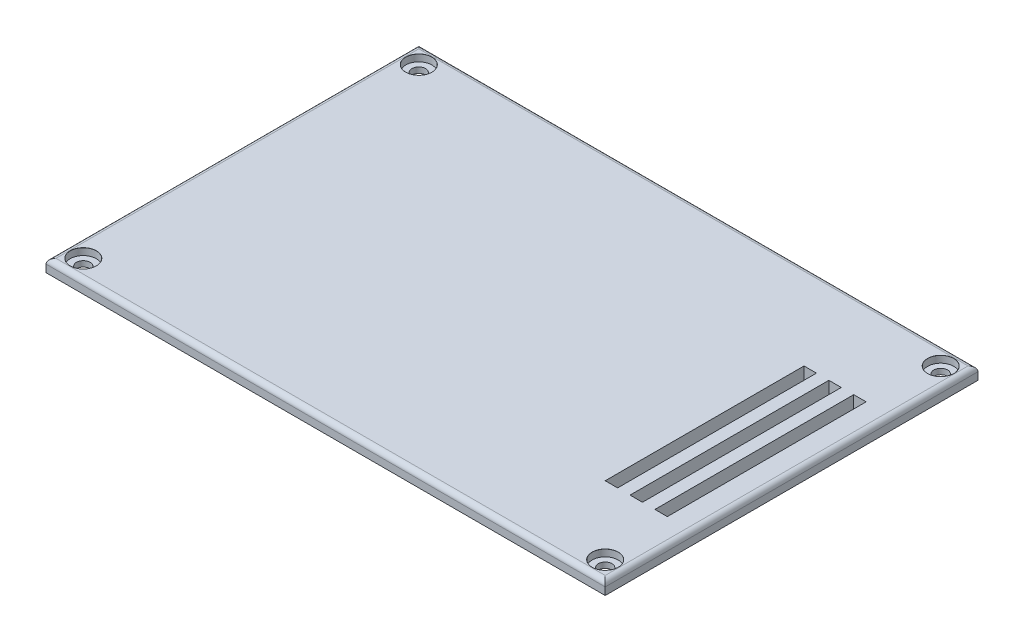
SolidWorks part; units mm, degrees
ref_plane "Front Plane" through (0, 0, 0) normal (0, 0, 1) x (1, 0, 0)
ref_plane "Top Plane" through (0, 0, 0) normal (0, 1, 0) x (1, 0, 0)
ref_plane "Right Plane" through (0, 0, 0) normal (1, 0, 0) x (0, 0, -1)
sketch "Sketch1" plane through (0, 0, 0) normal (0, 1, 0) x (1, 0, 0)
  line L1 (-112.5, 75) -> (112.5, 75)
  line L2 (-112.5, 75) -> (-112.5, -75)
  line L3 (-112.5, -75) -> (112.5, -75)
  line L4 (112.5, 75) -> (112.5, -75)
  line L5 (-112.5, 75) -> (112.5, -75) construction
  line L6 (-112.5, -75) -> (112.5, 75) construction
  line L7 (97.5, 40) -> (102.5, 40)
  line L8 (97.5, 40) -> (97.5, -40)
  line L9 (97.5, -40) -> (102.5, -40)
  line L10 (102.5, 40) -> (102.5, -40)
  line L11 (87.5, 40) -> (92.5, 40)
  line L12 (87.5, 40) -> (87.5, -40)
  line L13 (87.5, -40) -> (92.5, -40)
  line L14 (92.5, 40) -> (92.5, -40)
  line L15 (77.5, 40) -> (82.5, 40)
  line L16 (77.5, 40) -> (77.5, -40)
  line L17 (77.5, -40) -> (82.5, -40)
  line L18 (82.5, 40) -> (82.5, -40)
  point P0 (0, 0)
  point P18 (0, 0)
  point P19 (0, 0)
  point P20 (102.5, 0)
  point P21 (112.5, 0)
  dimension "D1" = 150
  dimension "D2" = 225
  dimension "D3" = 80
  dimension "D4" = 5
  dimension "D5" = 5
  dimension "D6" = 5
  dimension "D7" = 10
extrude "Boss-Extrude1" add sketch "Sketch1" along normal blind 5
hole_wizard "CBORE for M5 SBHCS1" positions "Sketch2" profile "Sketch3" counterbore size "M5" standard "ANSI Metric" end condition through all
sketch "Sketch2" plane through (0, 5, 0) normal (0, 1, 0) x (1, 0, 0)
  line L1 (-105, 67.5) -> (105, 67.5) construction
  line L2 (105, 67.5) -> (105, -67.5) construction
  line L3 (105, -67.5) -> (-105, -67.5) construction
  line L4 (-105, -67.5) -> (-105, 67.5) construction
  line L6 (-112.5, 75) -> (-112.5, -75) construction
  line L7 (112.5, -75) -> (112.5, 75) construction
  line L8 (112.5, 75) -> (-112.5, 75) construction
  line L9 (-112.5, -75) -> (112.5, -75) construction
  point P0 (-105, 67.5)
  point P2 (105, 67.5)
  point P4 (-105, -67.5)
  point P6 (105, -67.5)
  point P28 (97.5, -60)
  dimension "D1" = 7.5
  dimension "D2" = 7.5
  dimension "D3" = 7.5
  dimension "D4" = 7.5
sketch "Sketch3" plane through (-105, 5, -67.5) normal (1, 0, 0) x (0, 0, 1)
  line L0 (0, 0) -> (0, 5)
  line L1 (0, 5) -> (2.75, 5)
  line L3 (2.75, 5) -> (2.75, 2.75)
  line L4 (5.25, 2.75) -> (2.75, 2.75)
  line L5 (5.25, 2.75) -> (5.25, 0.025)
  line L6 (5.25, 0.025) -> (5.275, 0)
  line L7 (5.275, 0) -> (0, 0)
  line L8 (-5.25, 0.025) -> (-5.275, 0) construction
  line L11 (0, -6.35) -> (0, 107.95) construction
  dimension "Thru Hole Dia." = 5.5
  dimension "Thru Hole Depth" = 5
  dimension "C'Bore Dia." = 10.5
  dimension "C'Bore Depth" = 2.75
  dimension "Near C'Sink Dia." = 10.55
  dimension "Near C'Sink Angle" = 90
fillet "Fillet1" radius 2 4 edges at (112.5, 5, 0) (0, 5, -75) (-112.5, 5, 0) (0, 5, 75)
